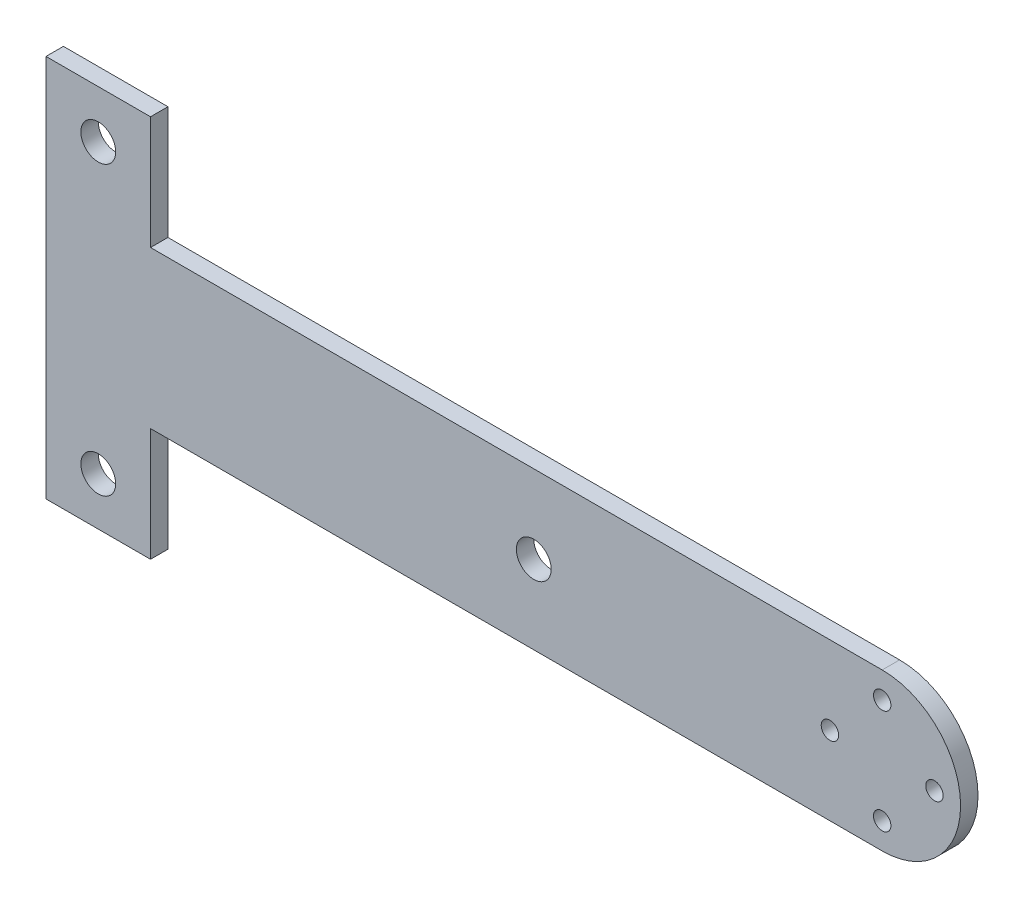
SolidWorks part; units mm, degrees
ref_plane "前视基准面" through (0, 0, 0) normal (0, 0, 1) x (1, 0, 0)
ref_plane "上视基准面" through (0, 0, 0) normal (0, 1, 0) x (1, 0, 0)
ref_plane "右视基准面" through (0, 0, 0) normal (1, 0, 0) x (0, 0, -1)
sketch "草图1" plane through (0, 0, 0) normal (0, 0, 1) x (1, 0, 0)
  line L0 (41.2764, 0.1457) -> (41.2764, 6.1457)
  line L1 (41.2764, -8.8543) -> (-42.7236, -8.8543)
  line L2 (41.2764, 9.1457) -> (-42.7236, 9.1457)
  line L3 (-42.7236, 9.1457) -> (-42.7236, 22.1457)
  line L4 (-42.7236, 22.1457) -> (-54.7236, 22.1457)
  line L5 (-54.7236, 22.1457) -> (-54.7236, -21.8543)
  line L6 (-54.7236, -21.8543) -> (-42.7236, -21.8543)
  line L7 (-42.7236, -21.8543) -> (-42.7236, -8.8543)
  circle A1 centre (1.2764, 0.1457) radius 2
  circle A2 centre (-48.7236, 16.6457) radius 2
  circle A3 centre (-48.7236, -16.3543) radius 2
  circle A4 centre (41.2764, 6.1457) radius 1
  circle A5 centre (47.2764, 0.1457) radius 1
  circle A6 centre (41.2764, -5.8543) radius 1
  circle A7 centre (35.2764, 0.1457) radius 1
  circle A8 centre (41.2764, 0.1457) radius 9 construction
  arc A9 (41.2764, 9.1457) -> (41.2764, -8.8543) centre (41.2764, 0.1457) cw
  dimension "D1" = 4
  dimension "D3" = 2
  dimension "D5" = 33
  dimension "D2" = 6
  dimension "D6" = 13
  dimension "D7" = 12
  dimension "D8" = 90
  dimension "D9" = 6
  dimension "D4" = 4
extrude "凸台-拉伸1" add sketch "草图1" along normal blind 2
